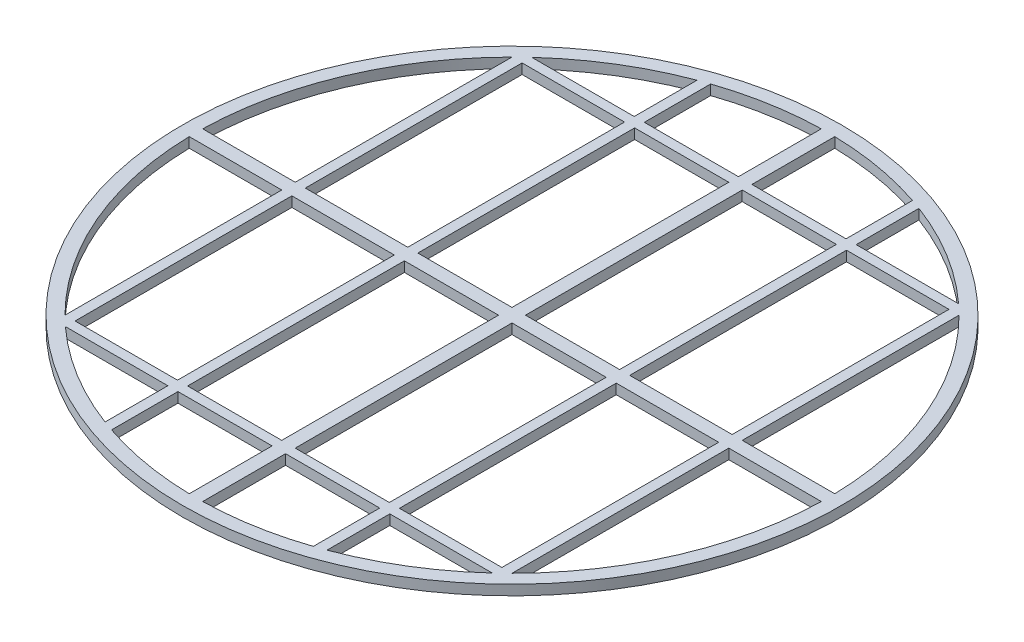
SolidWorks part; units mm, degrees
ref_plane "前视基准面" through (0, 0, 0) normal (0, 0, 1) x (1, 0, 0)
ref_plane "上视基准面" through (0, 0, 0) normal (0, 1, 0) x (1, 0, 0)
ref_plane "右视基准面" through (0, 0, 0) normal (1, 0, 0) x (0, 0, -1)
other "Configuration Table"
sketch "草图1" plane through (0, 0, 0) normal (0, 1, 0) x (1, 0, 0)
  line L0 (-93.9787, 2) -> (-2, 2)
  line L1 (-93.9787, -2) -> (-66.468, -2)
  line L2 (-112.7476, 0) -> (144.112, 0) construction
  line L3 (0, -124.1249) -> (0, 111.8251) construction
  line L4 (-2, 2) -> (-2, 93.9787)
  line L5 (2, 2) -> (2, 93.9787)
  line L6 (-2, -2) -> (-2, -93.9787)
  line L7 (2, -2) -> (2, -93.9787)
  line L8 (2, 2) -> (93.9787, 2)
  line L9 (2, -2) -> (30, -2)
  line L10 (-30, 2) -> (-30, 89.0842)
  line L11 (-33, 2) -> (-33, 88.017)
  line L12 (-63.468, 2) -> (-63.468, 69.3384)
  line L13 (-66.468, 2) -> (-66.468, 66.468)
  line L14 (30, 89.0842) -> (30, 2)
  line L15 (33, 88.017) -> (33, 2)
  line L16 (63.468, 69.3384) -> (63.468, 2)
  line L17 (66.468, 66.468) -> (66.468, 2)
  line L18 (66.468, -66.468) -> (66.468, -2)
  line L19 (63.468, -2) -> (63.468, -69.3384)
  line L20 (33, -2) -> (33, -88.017)
  line L21 (30, -2) -> (30, -89.0842)
  line L22 (-30, -2) -> (-30, -89.0842)
  line L23 (-33, -2) -> (-33, -88.017)
  line L24 (-63.468, -2) -> (-63.468, -69.3384)
  line L25 (-66.468, -2) -> (-66.468, -66.468)
  line L26 (-63.468, -2) -> (-33, -2)
  line L27 (-30, -2) -> (-2, -2)
  line L28 (66.468, -2) -> (93.9787, -2)
  line L29 (33, -2) -> (63.468, -2)
  circle A0 centre (0, 0) radius 98
  arc A1 (-93.9787, -2) -> (-66.468, -66.468) centre (0, 0) ccw
  arc A2 (93.9787, 2) -> (66.468, 66.468) centre (0, 0) ccw
  arc A3 (-2, 93.9787) -> (-30, 89.0842) centre (0, 0) ccw
  arc A4 (2, -93.9787) -> (30, -89.0842) centre (0, 0) ccw
  arc A5 (-66.468, 66.468) -> (-93.9787, 2) centre (0, 0) ccw
  arc A6 (-33, 88.017) -> (-63.468, 69.3384) centre (0, 0) ccw
  arc A7 (30, 89.0842) -> (2, 93.9787) centre (0, 0) ccw
  arc A8 (63.468, 69.3384) -> (33, 88.017) centre (0, 0) ccw
  arc A9 (-63.468, -69.3384) -> (-33, -88.017) centre (0, 0) ccw
  arc A10 (-30, -89.0842) -> (-2, -93.9787) centre (0, 0) ccw
  arc A11 (33, -88.017) -> (63.468, -69.3384) centre (0, 0) ccw
  arc A12 (66.468, -66.468) -> (93.9787, -2) centre (0, 0) ccw
  dimension "D1" = 196
  dimension "D2" = 188
  dimension "D3" = 2
  dimension "D4" = 2
  dimension "D5" = 2
  dimension "D6" = 2
  dimension "D7" = 3
  dimension "D8" = 28
  dimension "D9" = 3
  dimension "D10" = 3
  dimension "D11" = 28
  dimension "D12" = 3
  dimension "D13" = 91.1744
  dimension "D14" = 91.1744
  dimension "D15" = 90
extrude "凸台-拉伸1" add sketch "草图1" along normal blind 3
sketch "草图2" plane through (0, 3, 0) normal (0, 1, 0) x (1, 0, 0)
  line L0 (-66.468, 66.468) -> (66.468, 66.468)
  line L1 (-66.468, 2) -> (-66.468, 66.468) construction
  line L2 (66.468, 66.468) -> (63.468, 69.3384)
  line L3 (63.468, 69.3384) -> (-63.468, 69.3384)
  line L4 (-63.468, 69.3384) -> (-66.468, 66.468)
  line L5 (-66.468, -66.468) -> (66.468, -66.468)
  line L6 (66.468, -66.468) -> (63.468, -69.3384)
  line L7 (63.468, -69.3384) -> (-63.468, -69.3384)
  line L8 (-63.468, -69.3384) -> (-66.468, -66.468)
  arc A0 (-66.468, 66.468) -> (-93.9787, 2) centre (0, 0) ccw construction
extrude "凸台-拉伸2" add sketch "草图2" against normal blind 3
